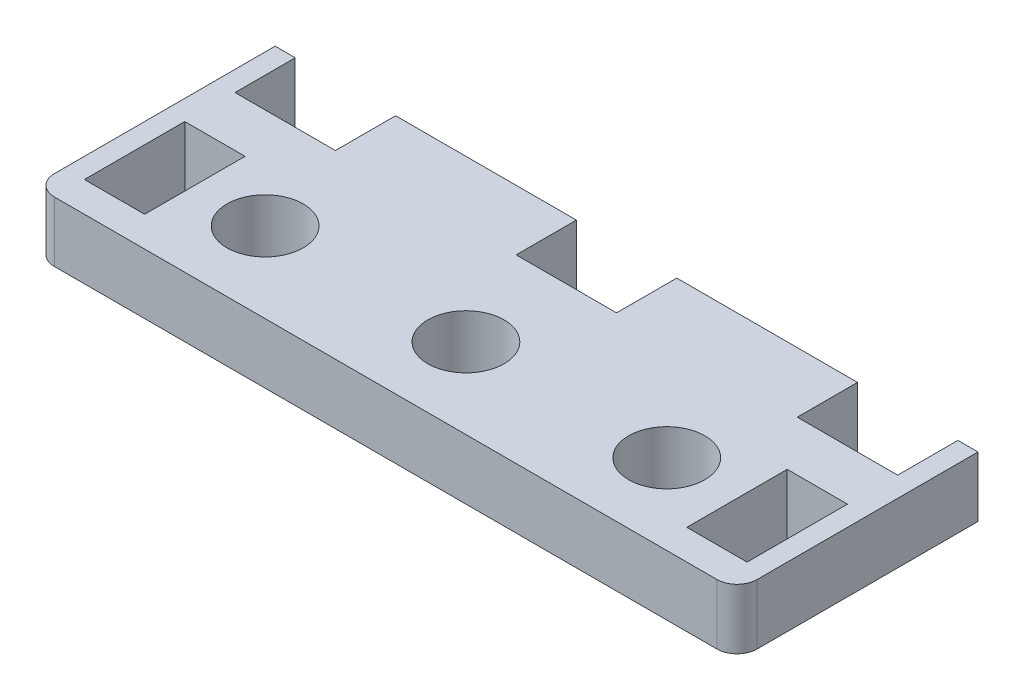
SolidWorks part; units mm, degrees
ref_plane "Front Plane" through (0, 0, 0) normal (0, 0, 1) x (1, 0, 0)
ref_plane "Top Plane" through (0, 0, 0) normal (0, 1, 0) x (1, 0, 0)
ref_plane "Right Plane" through (0, 0, 0) normal (1, 0, 0) x (0, 0, -1)
sketch "Sketch1" plane through (0, 0, 0) normal (0, 1, 0) x (1, 0, 0)
  line L1 (-17.5, 6) -> (17.5, 6)
  line L2 (-17.5, 6) -> (-17.5, -6)
  line L3 (-17.5, -6) -> (17.5, -6)
  line L4 (17.5, 6) -> (17.5, -6)
  line L5 (-17.5, 6) -> (17.5, -6) construction
  line L6 (-17.5, -6) -> (17.5, 6) construction
  point P0 (0, 0)
  dimension "D1" = 35
  dimension "D2" = 12
extrude "Boss-Extrude1" add sketch "Sketch1" along normal blind 3 contours L2 L3 L4 L1
sketch "Sketch5" plane through (0, 3, 0) normal (0, 1, 0) x (1, 0, 0)
  line L0 (-17.5, 6) -> (-17.5, -6) construction
  line L1 (-16.5, 0.5) -> (-13.5, 0.5)
  line L2 (-16.5, 0.5) -> (-16.5, -4.5)
  line L3 (-16.5, -4.5) -> (-13.5, -4.5)
  line L4 (-13.5, 0.5) -> (-13.5, -4.5)
  line L5 (-16.5, 0.5) -> (-13.5, -4.5) construction
  line L6 (-16.5, -4.5) -> (-13.5, 0.5) construction
  line L7 (13.5, 0.5) -> (16.5, 0.5)
  line L8 (13.5, 0.5) -> (13.5, -4.5)
  line L9 (13.5, -4.5) -> (16.5, -4.5)
  line L10 (16.5, 0.5) -> (16.5, -4.5)
  line L11 (13.5, 0.5) -> (16.5, -4.5) construction
  line L12 (13.5, -4.5) -> (16.5, 0.5) construction
  line L13 (17.5, 6) -> (17.5, -6) construction
  line L15 (-16.5, 6) -> (-11.5, 6)
  line L16 (-16.5, 6) -> (-16.5, 3)
  line L17 (-16.5, 3) -> (-11.5, 3)
  line L18 (-11.5, 6) -> (-11.5, 3)
  line L19 (-2.5, 6) -> (2.5, 6)
  line L20 (-2.5, 6) -> (-2.5, 3)
  line L21 (-2.5, 3) -> (2.5, 3)
  line L22 (2.5, 6) -> (2.5, 3)
  line L23 (11.5, 6) -> (16.5, 6)
  line L24 (11.5, 6) -> (11.5, 3)
  line L25 (11.5, 3) -> (16.5, 3)
  line L26 (16.5, 6) -> (16.5, 3)
  line L27 (-17.5, 6) -> (17.5, 6) construction
  point P0 (-15, -2)
  point P5 (15, -2)
  point P27 (0, 3)
  dimension "D1" = 3
  dimension "D2" = 5
  dimension "D3" = 3
  dimension "D4" = 5
  dimension "D5" = 1
  dimension "D6" = 1
  dimension "D7" = 3
  dimension "D8" = 1
  dimension "D9" = 1
  dimension "D11" = 2
extrude "Cut-Extrude1" cut sketch "Sketch5" against normal blind 3
fillet "Fillet1" radius 1 2 edges at (17.5, 1.5, 6) (-17.5, 1.5, 6)
hole_wizard "#6 Clearance Hole2" positions "Sketch6" profile "Sketch7" hole size "#6" standard "ANSI Inch" end condition through all
sketch "Sketch6" plane through (0, 3, 0) normal (0, 1, 0) x (1, 0, 0)
  point P0 (-10, -2)
  point P2 (0, -2)
  point P4 (10, -2)
  dimension "D1" = 2
  dimension "D2" = 10
  dimension "D3" = 10
sketch "Sketch7" plane through (-10, 3, 2) normal (1, 0, 0) x (0, 0, 1)
  line L0 (0, 0) -> (0, 3)
  line L1 (0, 3) -> (1.8986, 3)
  line L2 (1.8986, 3) -> (1.8986, 0)
  line L5 (1.8986, 0) -> (0, 0)
  line L11 (0, -6.35) -> (0, 107.95) construction
  dimension "Thru Hole Dia." = 3.7973
  dimension "Thru Hole Depth" = 3
equation "\"D3@Sketch5\"=\"D1@Sketch5\""
equation "\"D4@Sketch5\"=\"D2@Sketch5\""
equation "\"D6@Sketch5\"=\"D5@Sketch5\""
